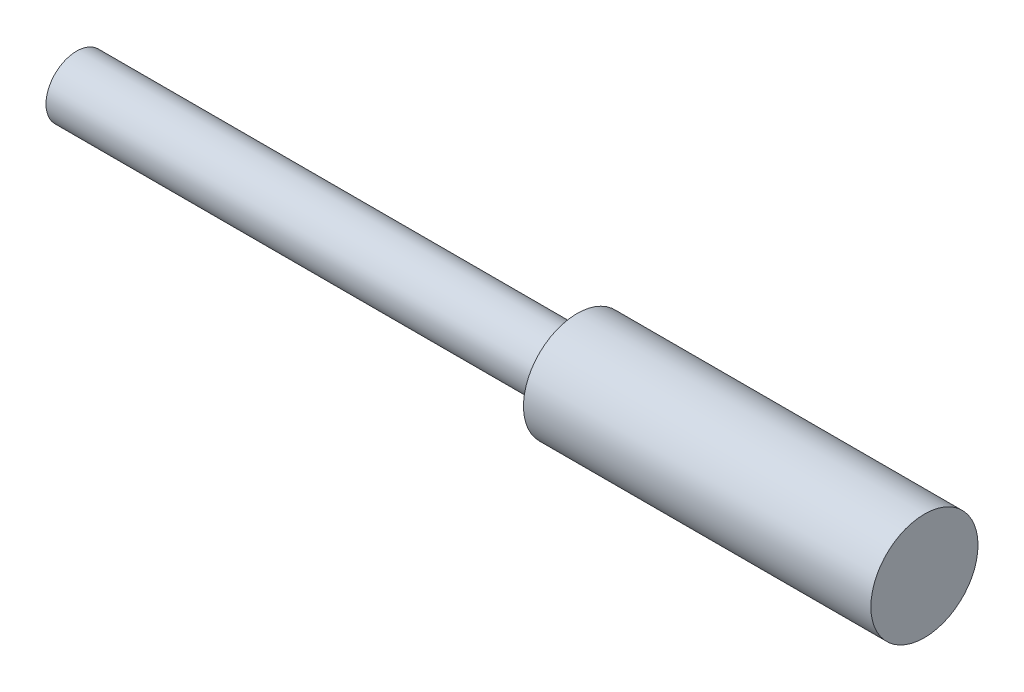
SolidWorks part; units mm, degrees
ref_plane "Front" through (0, 0, 0) normal (0, 0, 1) x (1, 0, 0)
ref_plane "Top" through (0, 0, 0) normal (0, 1, 0) x (1, 0, 0)
ref_plane "Right" through (0, 0, 0) normal (1, 0, 0) x (0, 0, -1)
sketch "Sketch3" plane through (2551.3496, 0, 0) normal (-1, 0, 0) x (0, 0, 1)
  circle A0 centre (20.1106, 11.5) radius 2 construction
  circle A1 centre (20.1106, 11.5) radius 2
extrude "Base-Extrude" add sketch "Sketch3" against normal up to surface (55.4 mm away)
sketch "Sketch4" plane through (2606.7496, 0, 0) normal (-1, 0, 0) x (0, 0, 1)
  circle A2 centre (20.1106, 11.5) radius 3.5
  dimension "D1" = 7
extrude "Boss-Extrude1" add sketch "Sketch4" along normal up to surface (22.7 mm away)
